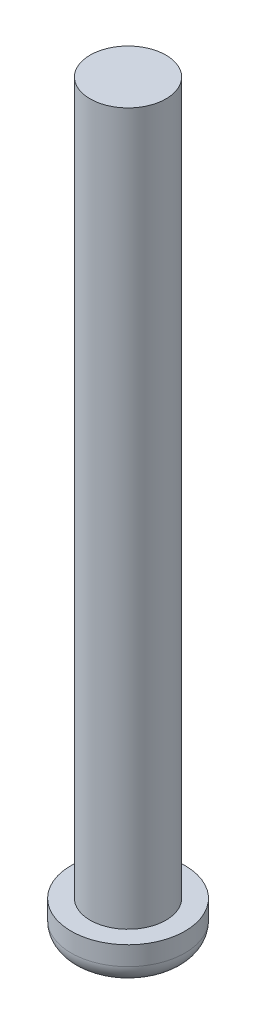
SolidWorks part; units mm, degrees
ref_plane "Alzado" through (0, 0, 0) normal (0, 0, 1) x (1, 0, 0)
ref_plane "Planta" through (0, 0, 0) normal (0, 1, 0) x (1, 0, 0)
ref_plane "Vista lateral" through (0, 0, 0) normal (1, 0, 0) x (0, 0, -1)
sketch "Croquis1" plane through (0, 0, 0) normal (0, 1, 0) x (1, 0, 0)
  circle A0 centre (0, 0) radius 4
  dimension "D1" = 8
extrude "Saliente-Extruir1" add sketch "Croquis1" along normal blind 75
sketch "Croquis2" plane through (0, 0, 0) normal (0, -1, 0) x (-1, 0, 0)
  circle A0 centre (0, 0) radius 6
extrude "Saliente-Extruir2" add sketch "Croquis2" along normal blind 4
fillet "Redondeo1" radius 2 1 edges at (0, -4, -6)
